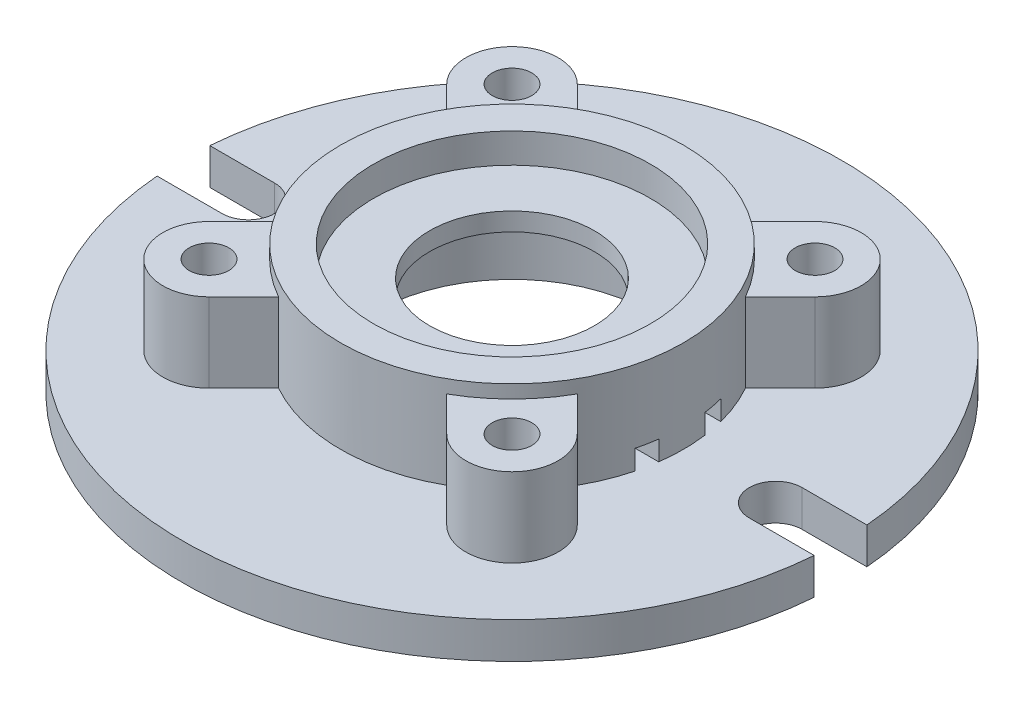
SolidWorks part; units mm, degrees
ref_plane "Front Plane" through (0, 0, 0) normal (0, 0, 1) x (1, 0, 0)
ref_plane "Top Plane" through (0, 0, 0) normal (0, 1, 0) x (1, 0, 0)
ref_plane "Right Plane" through (0, 0, 0) normal (1, 0, 0) x (0, 0, -1)
sketch "Sketch1" plane through (0, 0, 0) normal (0, 0, 1) x (1, 0, 0)
  line L0 (0, 0) -> (0, 39)
  line L1 (0, 39) -> (-52, 39)
  line L2 (-52, 39) -> (-52, 11)
  line L3 (-52, 11) -> (-100, 11)
  line L4 (-100, 11) -> (-100, 0)
  line L5 (-100, 0) -> (0, 0)
  dimension "D1" = 100
  dimension "D2" = 39
  dimension "D3" = 52
  dimension "D4" = 11
revolve "Revolve1" add sketch "Sketch1" angle 360 about L0
hole_wizard "Hole1" positions "Sketch2" profile "Sketch3" legacy end condition up to next
sketch "Sketch2" plane through (0, 39, 0) normal (0, 1, 0) x (1, 0, 0)
  point P0 (0, 0)
sketch "Sketch3" plane through (0, 39, 0) normal (1, 0, 0) x (0, 0, 1)
  line L0 (0, 0) -> (0, 39)
  line L1 (0, 39) -> (25, 39)
  line L2 (25, 39) -> (25, 9)
  line L3 (25, 9) -> (42, 9)
  line L4 (42, 9) -> (42, 0)
  line L5 (42, 0) -> (0, 0)
  line L6 (0, 110) -> (0, -10) construction
  dimension "Diameter" = 50
  dimension "Depth" = 39
  dimension "C-Bore Diameter" = 84
  dimension "C-Bore Depth" = 9
hole_wizard "Hole2" positions "Sketch4" profile "Sketch5" legacy
sketch "Sketch4" plane through (0, 0, 0) normal (0, -1, 0) x (-1, 0, 0)
  point P0 (0, 0)
sketch "Sketch5" plane through (0, 0, 0) normal (1, 0, 0) x (0, 0, -1)
  line L0 (0, 0) -> (0, 24.5)
  line L1 (0, 24.5) -> (42, 24.5)
  line L2 (42, 24.5) -> (42, 0)
  line L3 (42, 0) -> (0, 0)
  line L4 (0, 110) -> (0, -10) construction
  dimension "Diameter" = 84
  dimension "Depth" = 24.5
sketch "Sketch8" plane through (0, 11, 0) normal (0, 1, 0) x (1, 0, 0)
  line L0 (0, 0) -> (120.8897, 0) construction
  line L1 (0, 0) -> (76.7002, 76.7002) construction
  line L2 (25.5124, 45.3114) -> (36.0624, 55.8614)
  line L3 (45.3114, 25.5124) -> (55.8614, 36.0624)
  circle A0 centre (0, 0) radius 65 construction
  arc A1 (55.8614, 36.0624) -> (36.0624, 55.8614) centre (45.9619, 45.9619) ccw
  circle A2 centre (0, 0) radius 52 construction
  arc A3 (45.3114, 25.5124) -> (25.5124, 45.3114) centre (0, 0) ccw
  dimension "D2" = 130
  dimension "D3" = 28
  dimension "D1" = 45
extrude "Boss-Extrude1" add sketch "Sketch8" along normal blind 24
pattern_circular "CirPattern1" count 4 over 360 about axis through (0, 0, 0) along (0, 1, 0) of "Boss-Extrude1"
hole_wizard "Hole3" positions "Sketch9" profile "Sketch10" legacy
sketch "Sketch9" plane through (0, 35, 0) normal (0, 1, 0) x (1, 0, 0)
  point P0 (45.9619, 45.9619)
  point P3 (45.9619, -45.9619)
  point P6 (-45.9619, -45.9619)
  point P9 (-45.9619, 45.9619)
sketch "Sketch10" plane through (45.9619, 35, -45.9619) normal (1, 0, 0) x (0, 0, 1)
  line L0 (0, 0) -> (0, 24.5)
  line L1 (0, 24.5) -> (6, 24.5)
  line L2 (6, 24.5) -> (6, 0)
  line L3 (6, 0) -> (0, 0)
  line L4 (0, 110) -> (0, -10) construction
  dimension "Diameter" = 12
  dimension "Depth" = 24.5
sketch "Sketch11" plane through (0, 11, 0) normal (0, 1, 0) x (1, 0, 0)
  line L0 (0, 0) -> (142.1322, 0) construction
  line L1 (80, 0) -> (120, 0) construction
  line L2 (80, 8) -> (120, 8)
  line L3 (80, -8) -> (120, -8)
  arc A0 (80, 8) -> (80, -8) centre (80, 0) ccw
  arc A1 (120, -8) -> (120, 8) centre (120, 0) ccw
  circle A2 centre (0, 0) radius 100 construction
  point P5 (100, 0)
  point P10 (0, 0)
  point P11 (0, 0)
  point P12 (100, 0)
  dimension "D2" = 8
  dimension "D1" = 80
extrude "Cut-Extrude2" cut sketch "Sketch11" against normal blind 24
pattern_circular "CirPattern2" count 2 over 360 about axis through (0, 0, 0) along (0, 1, 0) of "Cut-Extrude2"
sketch "Sketch12" plane through (0, 0, 0) normal (1, 0, 0) x (0, 0, -1)
  line L0 (25.5124, 11) -> (-25.5124, 11) construction
  line L1 (-13, 11) -> (-7, 11)
  line L2 (-13, 11) -> (-13, 17)
  line L3 (-13, 17) -> (-7, 17)
  line L4 (-7, 11) -> (-7, 17)
  line L5 (0, 0) -> (0, 21.9196) construction
  line L6 (7, 11) -> (13, 11)
  line L7 (7, 11) -> (7, 17)
  line L8 (7, 17) -> (13, 17)
  line L9 (13, 11) -> (13, 17)
  dimension "D1" = 6
  dimension "D2" = 14
  dimension "D3" = 6
  dimension "D4" = 6
extrude "Cut-Extrude3" cut sketch "Sketch12" against normal through all both and the other way through all
